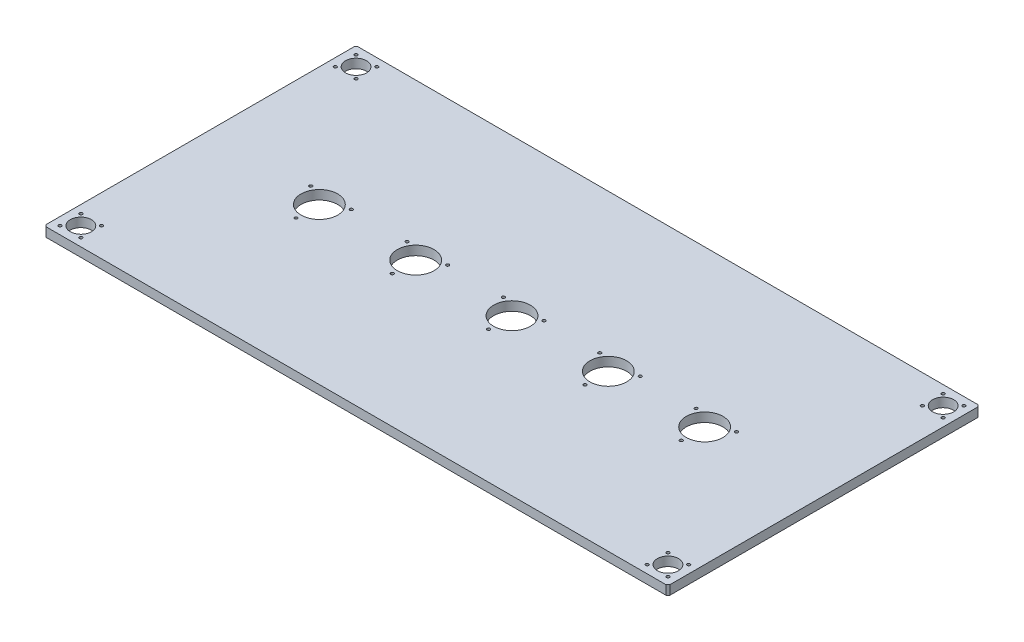
SolidWorks part; units mm, degrees
ref_plane "Front Plane" through (0, 0, 0) normal (0, 0, 1) x (1, 0, 0)
ref_plane "Top Plane" through (0, 0, 0) normal (0, 1, 0) x (1, 0, 0)
ref_plane "Right Plane" through (0, 0, 0) normal (1, 0, 0) x (0, 0, -1)
sketch "Sketch1" plane through (0, 0, 0) normal (0, 1, 0) x (1, 0, 0)
  line L0 (0, 0) -> (-340, 0) construction
  line L1 (340, 170) -> (-340, 170)
  line L2 (340, 170) -> (340, -170)
  line L3 (340, -170) -> (-340, -170)
  line L4 (-340, 170) -> (-340, -170)
  line L10 (340, 170) -> (-340, -170) construction
  line L11 (340, -170) -> (-340, 170) construction
  line L16 (0, 0) -> (0, -170) construction
  circle A4 centre (-320, -150) radius 11.5
  circle A7 centre (0, 0) radius 20
  circle A8 centre (-320, 150) radius 11.5
  circle A9 centre (320, 150) radius 11.5
  circle A10 centre (320, -150) radius 11.5
  circle A11 centre (-105, 0) radius 20
  circle A12 centre (-210, 0) radius 20
  circle A13 centre (105, 0) radius 20
  circle A14 centre (210, 0) radius 20
  point P0 (0, 0)
  dimension "D6" = 23
  dimension "D1" = 40
  dimension "D2" = 20
  dimension "D3" = 20
  dimension "D4" = 680
  dimension "D5" = 340
  dimension "D8" = 210
  dimension "D9" = 105
extrude "Boss-Extrude1" add sketch "Sketch1" along normal blind 10
chamfer "Chamfer1" distance 2 angle 45 4 edges at (340, 5, -170) (340, 5, 170) (-340, 5, 170) (-340, 5, -170)
sketch "Sketch2" plane through (0, 10, 0) normal (0, 1, 0) x (1, 0, 0)
  line L8 (-308.6863, -161.3137) -> (-331.3137, -161.3137)
  line L9 (-308.6863, -161.3137) -> (-308.6863, -138.6863)
  line L10 (-308.6863, -138.6863) -> (-331.3137, -138.6863)
  line L11 (-331.3137, -161.3137) -> (-331.3137, -138.6863)
  line L12 (-308.6863, -161.3137) -> (-331.3137, -138.6863) construction
  line L13 (-308.6863, -138.6863) -> (-331.3137, -161.3137) construction
  point P11 (-320, -150)
  dimension "D1" = 32
hole_wizard "M4x0.7 Tapped Hole1" positions "3DSketch1" profile "Sketch3" tap size "M4x0.7" standard "BSI" end condition through all
sketch3d "3DSketch1"
  point P0 (-331.3137, 10, 138.6863)
  point P3 (-308.6863, 10, 138.6863)
  point P6 (-308.6863, 10, 161.3137)
  point P9 (-331.3137, 10, 161.3137)
sketch "Sketch3" plane through (-331.3137, 10, 138.6863) normal (1, 0, 0) x (0, 0, 1)
  line L0 (0, 0) -> (0, 10)
  line L1 (0, 10) -> (1.65, 10)
  line L2 (1.65, 10) -> (1.65, 0)
  line L5 (1.65, 0) -> (0, 0)
  line L11 (0, -6.35) -> (0, 107.95) construction
  dimension "Thru Tap Drill Dia." = 3.3
  dimension "Thru Tap Drill Depth" = 10
cosmetic thread "Hole Thread4" parameters "D2"=4
cosmetic thread "Hole Thread5" parameters "D2"=4
cosmetic thread "Hole Thread6" parameters "D2"=4
cosmetic thread "Hole Thread7" parameters "D2"=4
mirror "Mirror1" about plane through (0, 0, 0) normal (0, 0, 1) of "M4x0.7 Tapped Hole1"
cosmetic thread "Hole Thread26" parameters "D2"=4
cosmetic thread "Hole Thread27" parameters "D2"=4
cosmetic thread "Hole Thread28" parameters "D2"=4
cosmetic thread "Hole Thread29" parameters "D2"=4
mirror "Mirror2" about plane through (0, 0, 0) normal (1, 0, 0) of "Mirror1", "M4x0.7 Tapped Hole1"
cosmetic thread "Hole Thread30" parameters "D2"=4
cosmetic thread "Hole Thread31" parameters "D2"=4
cosmetic thread "Hole Thread32" parameters "D2"=4
cosmetic thread "Hole Thread33" parameters "D2"=4
cosmetic thread "Hole Thread34" parameters "D2"=4
cosmetic thread "Hole Thread35" parameters "D2"=4
cosmetic thread "Hole Thread36" parameters "D2"=4
cosmetic thread "Hole Thread37" parameters "D2"=4
sketch "Sketch5" plane through (0, 10, 0) normal (0, 1, 0) x (1, 0, 0)
  line L0 (0, 0) -> (0, -25.5) construction
  line L1 (0, 0) -> (22.0836, 12.75) construction
  line L2 (0, 0) -> (-22.0836, 12.75) construction
  circle A0 centre (0, 0) radius 25.5
  dimension "D1" = 51
  dimension "D2" = 120
  dimension "D3" = 120
hole_wizard "M4x0.7 Tapped Hole2" positions "3DSketch2" profile "Sketch4" tap size "M4x0.7" standard "BSI" end condition through all
sketch3d "3DSketch2"
  line L7 (0, 10, 0) -> (-22.0836, 10, -12.75) construction
  line L8 (0, 10, 0) -> (22.0836, 10, -12.75) construction
  line L9 (0, 10, 0) -> (0, 10, 25.5) construction
  circle A0 centre (0, 10, 0) radius 25.5 construction
  point P3 (-22.0836, 10, -12.75)
  point P7 (0, 35.5, 0)
  point P8 (22.0836, 10, -12.75)
  point P10 (0, 10, 25.5)
sketch "Sketch4" plane through (-22.0836, 10, -12.75) normal (1, 0, 0) x (0, 0, 1)
  line L0 (0, 0) -> (0, 10)
  line L1 (0, 10) -> (1.65, 10)
  line L2 (1.65, 10) -> (1.65, 0)
  line L5 (1.65, 0) -> (0, 0)
  line L11 (0, -6.35) -> (0, 107.95) construction
  dimension "Thru Tap Drill Dia." = 3.3
  dimension "Thru Tap Drill Depth" = 10
cosmetic thread "Hole Thread8" parameters "D2"=4
cosmetic thread "Hole Thread20" parameters "D2"=4
cosmetic thread "Hole Thread21" parameters "D2"=4
pattern_linear "LPattern1" count 3 spacing 105 along (1, 0, 0) count 3 spacing 105 along (-1, 0, 0) of "M4x0.7 Tapped Hole2"
cosmetic thread "Hole Thread38" parameters "D2"=4
cosmetic thread "Hole Thread39" parameters "D2"=4
cosmetic thread "Hole Thread40" parameters "D2"=4
cosmetic thread "Hole Thread41" parameters "D2"=4
cosmetic thread "Hole Thread42" parameters "D2"=4
cosmetic thread "Hole Thread43" parameters "D2"=4
cosmetic thread "Hole Thread44" parameters "D2"=4
cosmetic thread "Hole Thread45" parameters "D2"=4
cosmetic thread "Hole Thread46" parameters "D2"=4
cosmetic thread "Hole Thread47" parameters "D2"=4
cosmetic thread "Hole Thread48" parameters "D2"=4
cosmetic thread "Hole Thread49" parameters "D2"=4
equation "\"D9@Sketch1\"=\"D8@Sketch1\"/2"
